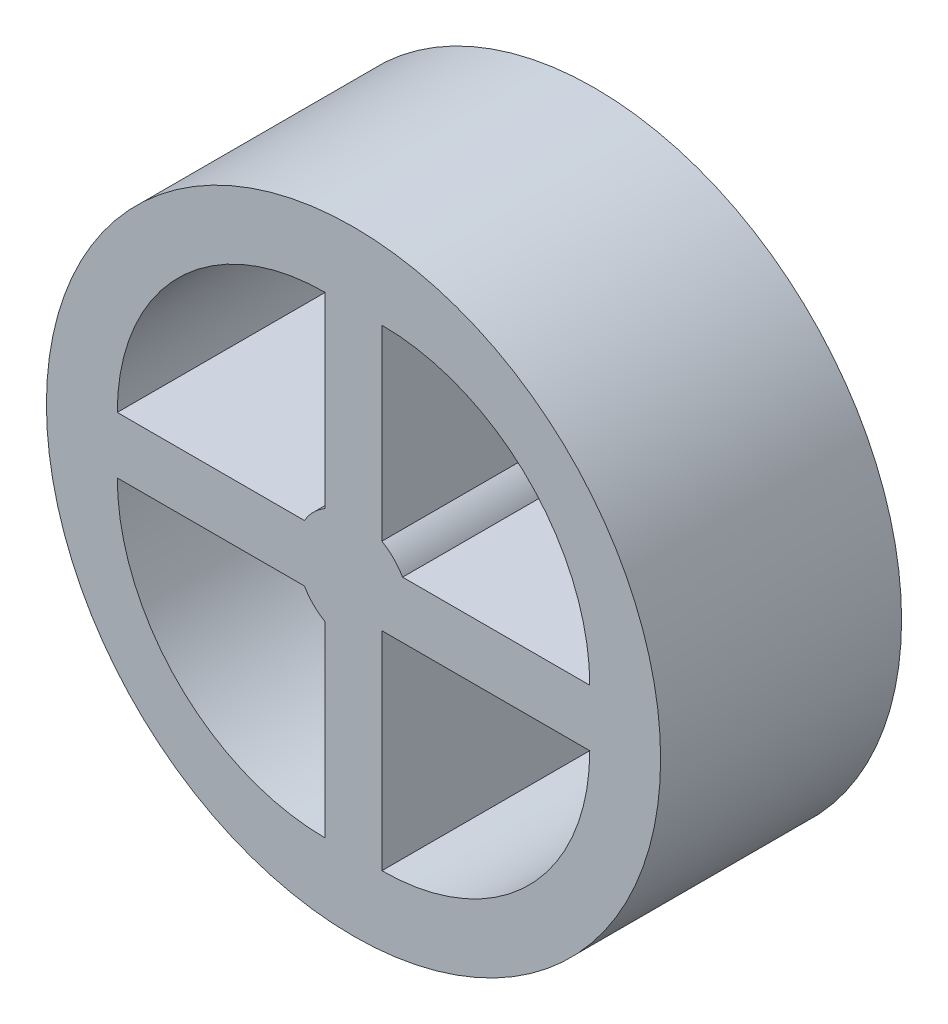
SolidWorks part; units mm, degrees
ref_plane "前视基准面" through (0, 0, 0) normal (0, 0, 1) x (1, 0, 0)
ref_plane "上视基准面" through (0, 0, 0) normal (0, 1, 0) x (1, 0, 0)
ref_plane "右视基准面" through (0, 0, 0) normal (1, 0, 0) x (0, 0, -1)
sketch "草图1" plane through (0, 0, 0) normal (0, 0, 1) x (1, 0, 0)
  circle A0 centre (0, 0) radius 325
  dimension "D1" = 650
extrude "凸台-拉伸1" add sketch "草图1" along normal blind 255
sketch "草图2" plane through (0, 0, 0) normal (0, 0, 1) x (1, 0, 0)
  line L1 (51.9615, 30) -> (250, 30)
  line L2 (30, 250) -> (30, 51.9615)
  arc A0 (51.9615, 30) -> (30, 51.9615) centre (0, 0) ccw
  arc A1 (30, 250) -> (250, 30) centre (30, 30) cw
  dimension "D1" = 120
  dimension "D2" = 30
  dimension "D3" = 30
  dimension "D4" = 220
extrude "切除-拉伸2" cut sketch "草图2" along normal blind 255
sketch "草图3" plane through (0, 0, 0) normal (0, 0, 1) x (1, 0, 0)
  line L1 (-30, 250) -> (-30, 51.9615)
  line L2 (-51.9615, 30) -> (-250, 30)
  arc A0 (-30, 51.9615) -> (-51.9615, 30) centre (0, 0) ccw
  arc A1 (-30, 250) -> (-250, 30) centre (-30, 30) ccw
  dimension "D1" = 120
  dimension "D2" = 30
  dimension "D4" = 220
extrude "切除-拉伸3" cut sketch "草图3" along normal blind 255
sketch "草图7" plane through (0, 0, 0) normal (0, 0, 1) x (1, 0, 0)
  line L0 (-30, -51.9615) -> (-30, -250)
  line L1 (-51.9615, -30) -> (-250, -30)
  arc A0 (-51.9615, -30) -> (-30, -51.9615) centre (0, 0) ccw
  arc A1 (-250, -30) -> (-30, -250) centre (-30, -30) ccw
  dimension "D1" = 30
  dimension "D2" = 220
  dimension "D3" = 220
extrude "切除-拉伸5" cut sketch "草图7" along normal blind 255
sketch "草图8" plane through (0, 0, 0) normal (0, 0, 1) x (1, 0, 0)
  line L0 (-51.9615, -30) -> (361.296, -30) construction
  line L1 (30, -30) -> (30, -250)
  line L2 (30, -5.323) -> (30, -357.9692) construction
  line L3 (250, 30) -> (250, -276.794) construction
  line L4 (-30, -250) -> (242.1947, -250) construction
  line L5 (30, -30) -> (250, -30)
  arc A0 (250, -30) -> (30, -250) centre (30, -30) cw
extrude "切除-拉伸6" cut sketch "草图8" along normal blind 255
